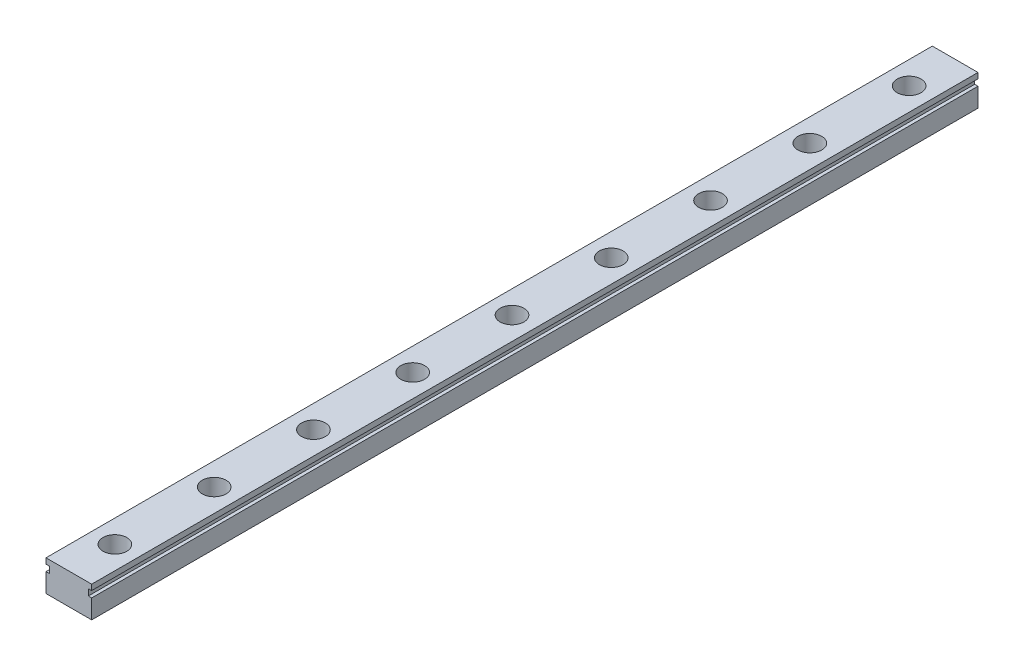
SolidWorks part; units mm, degrees
ref_plane "Front Plane" through (0, 0, 0) normal (0, 0, 1) x (1, 0, 0)
ref_plane "Top Plane" through (0, 0, 0) normal (0, 1, 0) x (1, 0, 0)
ref_plane "Right Plane" through (0, 0, 0) normal (1, 0, 0) x (0, 0, -1)
sketch "Sketch1" plane through (0, 0, 0) normal (0, 0, 1) x (1, 0, 0)
  line L1 (-5.75, -3.9) -> (5.75, -3.9)
  line L2 (-5.75, -3.9) -> (-5.75, 3.9)
  line L3 (-5.75, 3.9) -> (5.75, 3.9)
  line L4 (5.75, -3.9) -> (5.75, 3.9)
  line L5 (-5.75, -3.9) -> (5.75, 3.9) construction
  line L6 (-5.75, 3.9) -> (5.75, -3.9) construction
  point P0 (0, 0)
  dimension "D1" = 11.5
  dimension "D2" = 7.8
extrude "Boss-Extrude1" add sketch "Sketch1" along normal blind 223.2
sketch "Sketch2" plane through (0, 0, 223.2) normal (0, 0, 1) x (1, 0, 0)
  line L0 (5.75, -3.9) -> (5.75, 3.9) construction
  line L1 (5.75, 2.5) -> (4.9147, 2.5)
  line L2 (5.75, 2.5) -> (5.75, 0.9)
  line L3 (5.75, 0.9) -> (4.9147, 0.9)
  line L4 (4.9147, 2.5) -> (4.9147, 0.9)
  line L5 (5.75, 3.9) -> (-5.75, 3.9) construction
  line L7 (0, -4.29) -> (0, 4.29) construction
  line L8 (-5.75, 0.9) -> (-4.9147, 0.9)
  line L9 (-4.9147, 2.5) -> (-4.9147, 0.9)
  line L10 (-5.75, 2.5) -> (-4.9147, 2.5)
  line L11 (-5.75, 2.5) -> (-5.75, 0.9)
  dimension "D1" = 1.4
  dimension "D2" = 1.6
extrude "Cut-Extrude1" cut sketch "Sketch2" against normal through all
sketch "Sketch3" plane through (0, 3.9, 0) normal (0, 1, 0) x (1, 0, 0)
  line L0 (0, -223.2) -> (0, -215.9183) construction
  line L2 (5.75, -223.2) -> (-5.75, -223.2) construction
  circle A0 centre (0, -211.6) radius 3
  circle A1 centre (0, -186.6) radius 3
  circle A2 centre (0, -161.6) radius 3
  circle A3 centre (0, -136.6) radius 3
  circle A4 centre (0, -111.6) radius 3
  circle A5 centre (0, -86.6) radius 3
  circle A6 centre (0, -61.6) radius 3
  circle A7 centre (0, -36.6) radius 3
  circle A8 centre (0, -11.6) radius 3
  dimension "D1" = 11.6
  dimension "D2" = 6
  dimension "D3" = 9
extrude "Cut-Extrude2" cut sketch "Sketch3" against normal blind 4.7
sketch "Sketch4" plane through (0, -0.8, 0) normal (0, 1, 0) x (1, 0, 0)
  circle A0 centre (0, -211.6) radius 1.7
  circle A1 centre (0, -186.6) radius 1.7
  circle A2 centre (0, -161.6) radius 1.7
  circle A3 centre (0, -136.6) radius 1.7
  circle A4 centre (0, -111.6) radius 1.7
  circle A5 centre (0, -86.6) radius 1.7
  circle A6 centre (0, -61.6) radius 1.7
  circle A7 centre (0, -36.6) radius 1.7
  circle A8 centre (0, -11.6) radius 1.7
  dimension "D1" = 3.4
  dimension "D2" = 9
extrude "Cut-Extrude3" cut sketch "Sketch4" against normal through all
